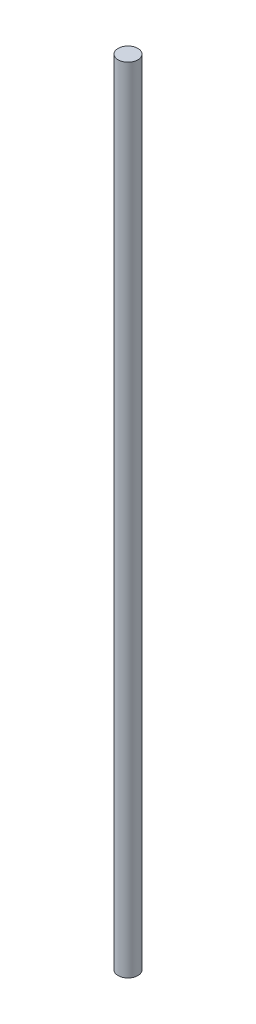
SolidWorks part; units mm, degrees
ref_plane "Front Plane" through (0, 0, 0) normal (0, 0, 1) x (1, 0, 0)
ref_plane "Top Plane" through (0, 0, 0) normal (0, 1, 0) x (1, 0, 0)
ref_plane "Right Plane" through (0, 0, 0) normal (1, 0, 0) x (0, 0, -1)
sketch "Sketch1" plane through (0, 0, 0) normal (0, 1, 0) x (1, 0, 0)
  circle A0 centre (0, 0) radius 1.5
  dimension "D1" = 3
extrude "Boss-Extrude1" add sketch "Sketch1" along normal blind 120
